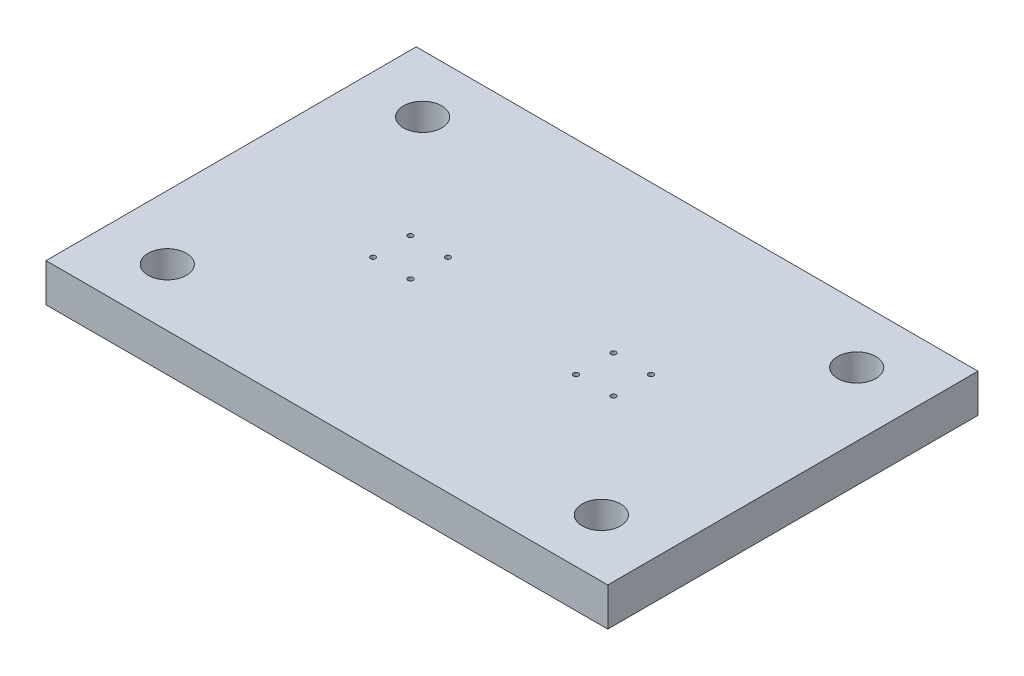
SolidWorks part; units mm, degrees
ref_plane "Front Plane" through (0, 0, 0) normal (0, 0, 1) x (1, 0, 0)
ref_plane "Top Plane" through (0, 0, 0) normal (0, 1, 0) x (1, 0, 0)
ref_plane "Right Plane" through (0, 0, 0) normal (1, 0, 0) x (0, 0, -1)
sketch "Sketch1" plane through (0, 0, 0) normal (0, 1, 0) x (1, 0, 0)
  line L1 (-440, 290) -> (440, 290)
  line L2 (-440, 290) -> (-440, -290)
  line L3 (-440, -290) -> (440, -290)
  line L4 (440, 290) -> (440, -290)
  line L6 (-440, 0) -> (440, 0) construction
  point P0 (0, 0)
extrude "Boss-Extrude1" add sketch "Sketch1" along normal blind 60
sketch "Sketch2" plane through (0, 60, 0) normal (0, 1, 0) x (1, 0, 0)
  circle A0 centre (-340, 200) radius 30
  circle A1 centre (340, 200) radius 30
  circle A2 centre (340, -200) radius 30
  circle A3 centre (-340, -200) radius 30
  dimension "D1" = 200
  dimension "D2" = 200
  dimension "D3" = 680
  dimension "D4" = 340
extrude "Cut-Extrude1" cut sketch "Sketch2" against normal blind 260
sketch "Sketch4" plane through (0, 60, 0) normal (0, 1, 0) x (1, 0, 0)
  circle A0 centre (-129.6551, 29.3449) radius 4
  circle A1 centre (-129.6551, -29.3449) radius 4
  circle A2 centre (-188.3449, -29.3449) radius 4
  circle A3 centre (-188.3449, 29.3449) radius 4
  circle A4 centre (188.3449, 29.3449) radius 4
  circle A5 centre (188.3449, -29.3449) radius 4
  circle A6 centre (129.6551, -29.3449) radius 4
  circle A7 centre (129.6551, 29.3449) radius 4
  point P0 (-159, 0)
  point P13 (-159, 0)
  point P21 (159, 0)
  dimension "D2" = 4
  dimension "D1" = 159
extrude "Cut-Extrude3" cut sketch "Sketch4" against normal blind 260
